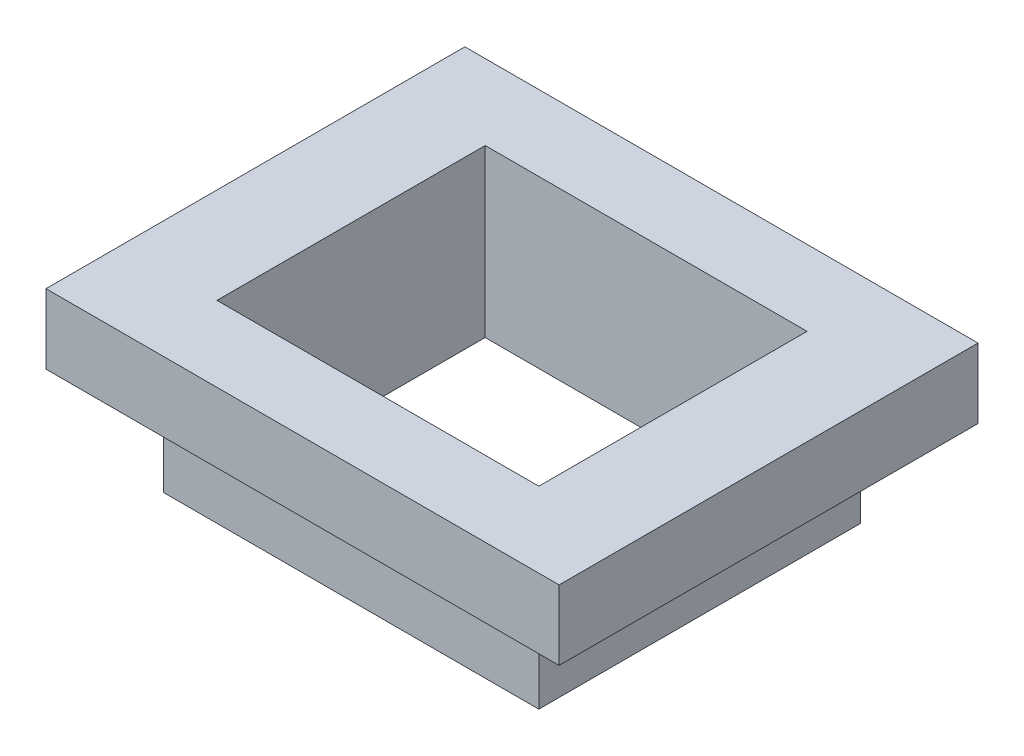
SolidWorks part; units mm, degrees
ref_plane "Front Plane" through (0, 0, 0) normal (0, 0, 1) x (1, 0, 0)
ref_plane "Top Plane" through (0, 0, 0) normal (0, 1, 0) x (1, 0, 0)
ref_plane "Right Plane" through (0, 0, 0) normal (1, 0, 0) x (0, 0, -1)
sketch "Sketch1" plane through (0, 0, 0) normal (0, 1, 0) x (1, 0, 0)
  line L1 (-460.9783, 161.3424) -> (495.5517, 161.3424)
  line L2 (-460.9783, 161.3424) -> (-460.9783, -619.5376)
  line L3 (-460.9783, -619.5376) -> (495.5517, -619.5376)
  line L4 (495.5517, 161.3424) -> (495.5517, -619.5376)
  line L8 (17.2867, 20.9024) -> (317.2867, 20.9024)
  line L9 (317.2867, -229.0976) -> (317.2867, 20.9024)
  line L12 (17.2867, 20.9024) -> (-282.7133, 20.9024)
  line L13 (-282.7133, -229.0976) -> (-282.7133, 20.9024)
  line L16 (17.2867, -479.0976) -> (-282.7133, -479.0976)
  line L17 (-282.7133, -229.0976) -> (-282.7133, -479.0976)
  line L20 (17.2867, -479.0976) -> (317.2867, -479.0976)
  line L21 (317.2867, -229.0976) -> (317.2867, -479.0976)
  dimension "D1" = 956.53
  dimension "D2" = 780.88
  dimension "D3" = 300
  dimension "D4" = 300
  dimension "D5" = 250
  dimension "D6" = 250
extrude "Boss-Extrude1" add sketch "Sketch1" along normal blind 130
sketch "Sketch2" plane through (0, 0, 0) normal (0, -1, 0) x (1, 0, 0)
  line L0 (367.2867, -20.9024) -> (367.2867, -70.9024)
  line L2 (-282.7133, 479.0976) -> (-282.7133, -20.9024)
  line L3 (-282.7133, -70.9024) -> (-332.7133, -70.9024)
  line L4 (-332.7133, 479.0976) -> (-332.7133, -70.9024)
  line L5 (-282.7133, 479.0976) -> (317.2867, 479.0976)
  line L6 (-332.7133, 479.0976) -> (-332.7133, 529.0976)
  line L7 (-332.7133, 529.0976) -> (367.2867, 529.0976)
  line L8 (367.2867, 479.0976) -> (367.2867, 529.0976)
  line L9 (-282.7133, -20.9024) -> (317.2867, -20.9024)
  line L11 (-282.7133, -70.9024) -> (367.2867, -70.9024)
  line L14 (367.2867, 479.0976) -> (367.2867, -20.9024)
  line L15 (367.2867, -20.9024) -> (317.2867, -20.9024)
  line L16 (317.2867, 479.0976) -> (317.2867, -20.9024)
  dimension "D1" = 50
  dimension "D2" = 50
  dimension "D3" = 50
  dimension "D4" = 50
extrude "Boss-Extrude2" add sketch "Sketch2" along normal blind 180
